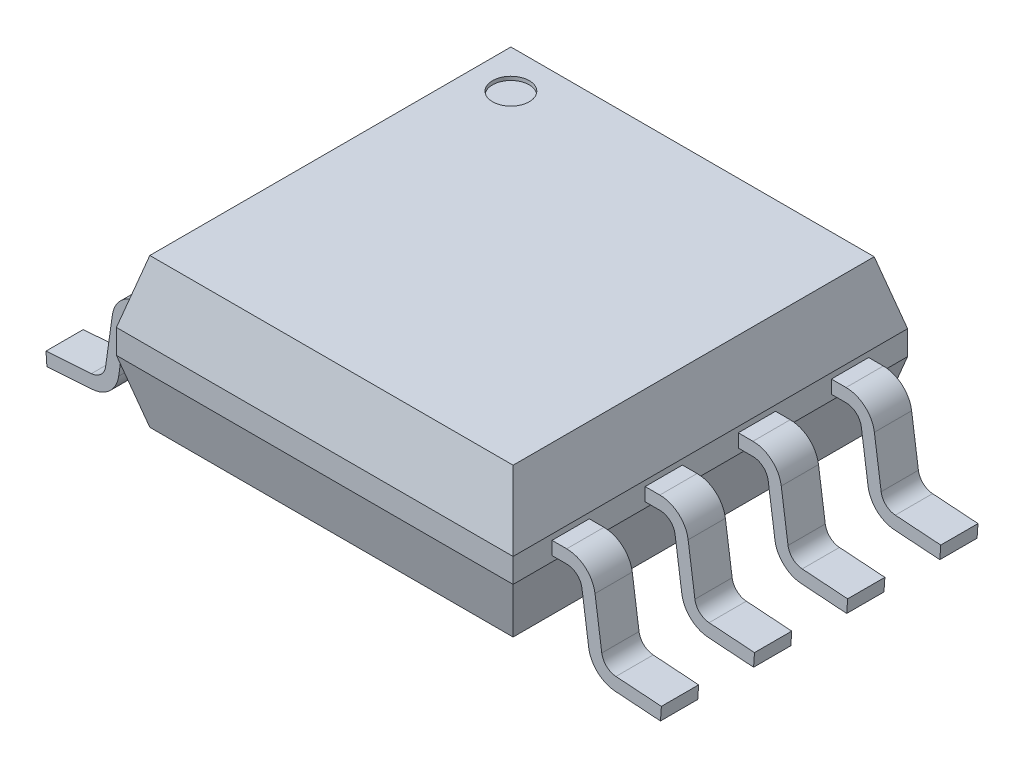
SolidWorks part; units mm, degrees
ref_plane "FRONT" through (0, 0, 0) normal (0, 0, 1) x (1, 0, 0)
ref_plane "TOP" through (0, 0, 0) normal (0, 1, 0) x (1, 0, 0)
ref_plane "RIGHT" through (0, 0, 0) normal (1, 0, 0) x (0, 0, -1)
sketch "Sketch1" plane through (0, 0, 0) normal (0, 1, 0) x (1, 0, 0)
  line L0 (0, 0) -> (0, 2.69) construction
  line L1 (-2.705, 2.69) -> (2.705, 2.69)
  line L2 (-2.705, 2.69) -> (-2.705, -2.69)
  line L3 (-2.705, -2.69) -> (2.705, -2.69)
  line L4 (2.705, 2.69) -> (2.705, -2.69)
  line L5 (0, 0) -> (2.705, 0) construction
  dimension "D1" = 5.41
  dimension "D2" = 5.38
extrude "Base-Extrude" add sketch "Sketch1" against normal blind 2.03
ref_plane "LEG PLANE" through (0, 0, -1.905) normal (0, 0, 1) x (1, 0, 0)
sketch "Sketch2" plane through (0, 0, -1.905) normal (0, 0, 1) x (1, 0, 0)
  line L0 (-2.705, -1.015) -> (-2.905, -1.015)
  line L1 (-2.705, -2.03) -> (-2.705, 0) construction
  line L2 (-3.2021, -1.2732) -> (-3.2943, -1.9292)
  line L3 (-3.5704, -2.1867) -> (-4.19, -2.23)
  line L5 (0, 0) -> (0, 1.3276) construction
  line L6 (-2.705, -1.015) -> (-0.9713, -1.015) construction
  line L8 (-2.705, -2.03) -> (2.705, -2.03) construction
  arc A0 (-2.905, -1.015) -> (-3.2021, -1.2732) centre (-2.905, -1.315) ccw
  arc A1 (-3.5704, -2.1867) -> (-3.2943, -1.9292) centre (-3.5913, -1.8874) ccw
  dimension "D4" = 0.3
  dimension "D7" = 0.3
  dimension "D1" = 4
  dimension "D2" = 0.2
  dimension "D3" = 8.38
  dimension "D5" = 8
  dimension "D6" = 0.2
extrude "PIN 1" add sketch "Sketch2" along normal mid plane 0.508 thin thin type mid plane wall 0.18
mirror "PIN 8" about plane through (0, 0, 0) normal (1, 0, 0) of "PIN 1"
pattern_linear "LPattern1" count 4 spacing 1.27 along (0, 0, 1) of "PIN 8", "PIN 1"
chamfer "TOP CHAMFER" distance 0.85 angle 15 4 edges at (0, 0, -2.69) (2.705, 0, 0) (0, 0, 2.69) (-2.705, 0, 0)
chamfer "BOTTOM CHAMFER" distance 0.85 angle 15 4 edges at (2.705, -2.03, 0) (0, -2.03, -2.69) (-2.705, -2.03, 0) (0, -2.03, 2.69)
sketch "Sketch3" plane through (0, 0, 0) normal (0, 1, 0) x (-1, 0, 0)
  line L0 (2.705, -2.69) -> (-2.705, -2.69) construction
  line L1 (2.705, 2.69) -> (2.705, -2.69) construction
  circle A0 centre (1.955, -1.94) radius 0.25
  dimension "D1" = 0.5
  dimension "D2" = 0.75
  dimension "D3" = 0.75
extrude "PIN1 HOL" cut sketch "Sketch3" against normal blind 0.05
